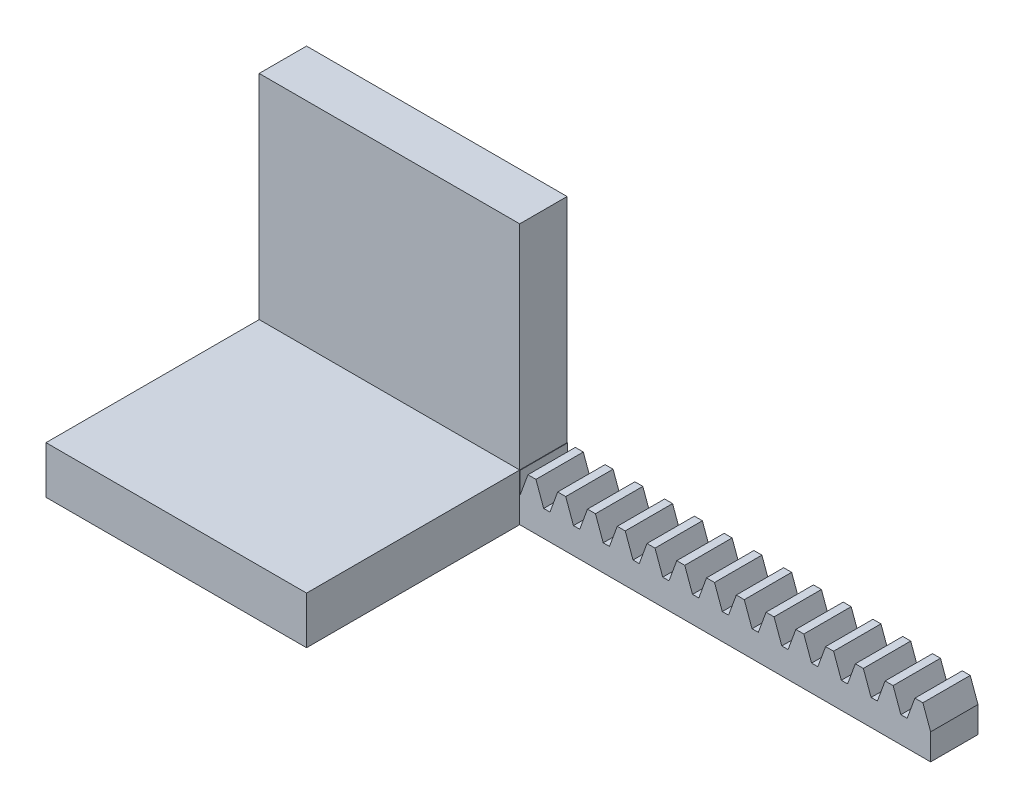
SolidWorks part; units mm, degrees
ref_plane "前视基准面" through (0, 0, 0) normal (0, 0, 1) x (1, 0, 0)
ref_plane "上视基准面" through (0, 0, 0) normal (0, 1, 0) x (1, 0, 0)
ref_plane "右视基准面" through (0, 0, 0) normal (1, 0, 0) x (0, 0, -1)
sketch "草图2" plane through (0, 0, 0) normal (0, 1, 0) x (1, 0, 0)
  line L1 (43.3214, -5) -> (-43.3214, -5)
  line L2 (43.3214, -5) -> (43.3214, 5)
  line L3 (43.3214, 5) -> (-43.3214, 5)
  line L4 (-43.3214, -5) -> (-43.3214, 5)
  line L5 (43.3214, -5) -> (-43.3214, 5) construction
  line L6 (43.3214, 5) -> (-43.3214, -5) construction
  point P0 (0, 0)
  dimension "D1" = 10
  dimension "D2" = 86.6429
extrude "凸台-拉伸1" add sketch "草图2" against normal blind 5.5
sketch "草图3" plane through (0, 0, 0) normal (0, 0, 1) x (1, 0, 0)
  line L0 (-43.3214, 0) -> (-41.6836, 4.5)
  line L1 (-41.6836, 4.5) -> (-39.9978, 4.5)
  line L2 (-39.9978, 4.5) -> (-38.36, 0)
  line L3 (-43.3214, 0) -> (43.3214, 0) construction
  line L4 (-38.36, 0) -> (-43.3214, 0)
  line L5 (-40.8407, 4.5) -> (-40.8407, 0) construction
  line L6 (-42.4115, 2.5) -> (-39.2699, 2.5) construction
  dimension "D1" = 2
  dimension "D2" = 2.5
  dimension "D3" = 40
  dimension "D4" = 3.1416
extrude "凸台-拉伸2" add sketch "草图3" along normal mid plane 10
pattern_linear "阵列(线性)1" count 14 spacing 6.2832 along (1, 0, 0) of "凸台-拉伸2"
sketch "草图5" plane through (0, 0, 0) normal (0, 0, 1) x (1, 0, 0)
  line L0 (-38.36, 0) -> (-37.0382, 0) construction
  line L1 (-38.36, 0) -> (-37.0382, 0)
  dimension "D1" = 1.3217
sketch "草图6" plane through (-43.3214, 0, 0) normal (-1, 0, 0) x (0, 0, 1)
  line L1 (5, -5.5) -> (-5, -5.5)
  line L2 (5, -5.5) -> (5, 4.5)
  line L3 (5, 4.5) -> (-5, 4.5)
  line L4 (-5, -5.5) -> (-5, 4.5)
extrude "凸台-拉伸3" add sketch "草图6" along normal blind 0.1
sketch "草图7" plane through (-43.4214, 0, 0) normal (-1, 0, 0) x (0, 0, 1)
  line L1 (-5, -5.5) -> (50, -5.5)
  line L2 (-5, -5.5) -> (-5, 4.5)
  line L3 (5, 4.5) -> (50, 4.5)
  line L4 (50, -5.5) -> (50, 4.5)
  line L5 (-5, -5.5) -> (5, -5.5)
  line L6 (-5, -5.5) -> (-5, 49.5)
  line L7 (-5, 49.5) -> (5, 49.5)
  line L8 (5, 4.5) -> (5, 49.5)
  line M9 (5, -5.5) -> (5, 4.5)
  line M10 (5, 4.5) -> (-5, 4.5)
  line M11 (-5, 4.5) -> (-5, -5.5)
  line M12 (-5, -5.5) -> (5, -5.5)
  dimension "D1" = 10
  dimension "D2" = 10
  dimension "D3" = 55
  dimension "D4" = 55
extrude "凸台-拉伸4" add sketch "草图7" along normal blind 55 contours L1 L4 L3 M9 | M12 M9 M10 M11 | L8 L7 L6 M10
equation "\"模数\"= 2"
equation "\"齿数\"=14"
equation "\"压力角\"= 20"
equation "\"宽度\"= 20'齿条的宽度"
equation "\"高度\"= 10'齿条的总高度（从齿顶到最底面）"
equation "\"D1@草图3\"=\"模数\""
equation "\"D2@草图3\"=\"模数\"*1.25"
equation "\"D3@草图3\"=\"压力角\"*2"
equation "\"D4@草图3\"=\"模数\"*pi*0.5"
equation "\"D1@阵列(线性)1\"= \"齿数\""
equation "\"D3@阵列(线性)1\"=\"模数\"*pi"
equation "\"D1@草图2\"=10"
equation "\"D1@凸台-拉伸2\"=10"
equation "\"D2@草图2\" = \"模数\" * \"齿数\" * pi - \"D1@草图5\""
equation "\"D1@凸台-拉伸1\" = \"高度\" - \"模数\" * 2.25"
